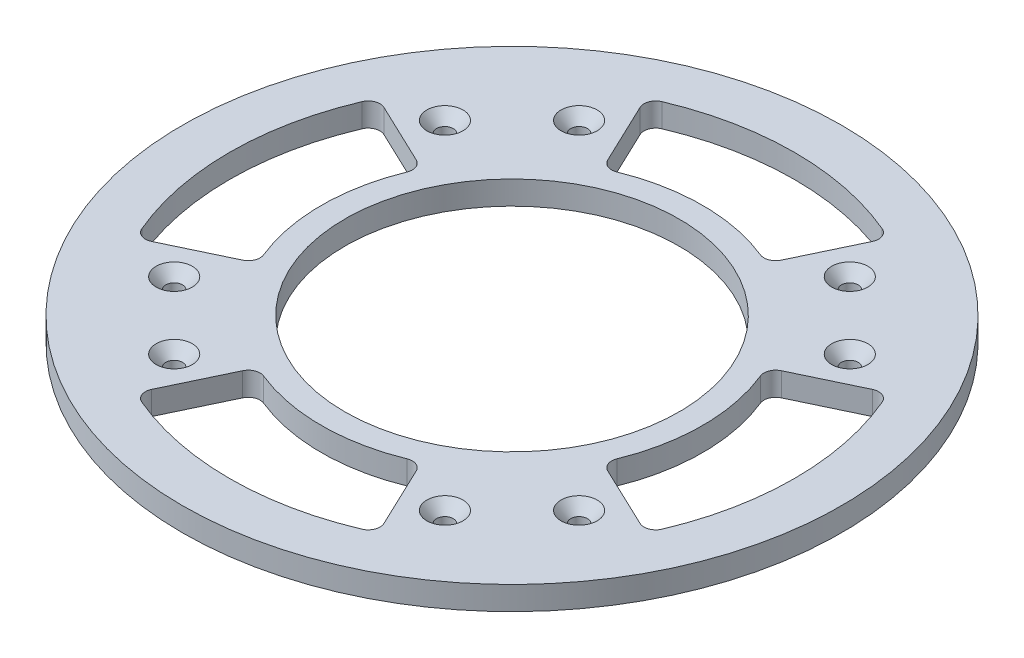
SolidWorks part; units mm, degrees
material "6061-T6 (SS)"
ref_plane "Front Plane" through (0, 0, 0) normal (0, 0, 1) x (1, 0, 0)
ref_plane "Top Plane" through (0, 0, 0) normal (0, 1, 0) x (1, 0, 0)
ref_plane "Right Plane" through (0, 0, 0) normal (1, 0, 0) x (0, 0, -1)
sketch "Sketch1" plane through (0, 0, 0) normal (0, 1, 0) x (1, 0, 0)
  line L5 (-85.725, -85.725) -> (85.725, 85.725) construction
  line L6 (-85.725, 85.725) -> (85.725, -85.725) construction
  circle A0 centre (0, 0) radius 54.61 construction
  circle A1 centre (0, 0) radius 88.9
  point P0 (0, 0)
  point P16 (-67.31, 0)
  point P18 (0, 76.2)
  dimension "D4" = 109.22
  dimension "D7" = 177.8
  dimension "D1" = 171.45
  dimension "D2" = 171.45
extrude "Boss-Extrude1" add sketch "Sketch1" along normal blind 6.35
hole_wizard "CSK for #8 Flat Head Machine Screw1" positions "Sketch3" profile "Sketch2" countersink size "#8" standard "ANSI Inch" end condition through all
sketch "Sketch3" plane through (0, 6.35, 0) normal (0, 1, 0) x (-1, 0, 0)
  line L0 (-36.5125, -54.61) -> (0, 0) construction
  line L1 (0, 0) -> (36.5125, -54.61) construction
  line L2 (36.5125, -54.61) -> (-36.5125, -54.61) construction
  line L5 (-54.61, -36.5125) -> (-54.61, 36.5125) construction
  line L8 (0, 0) -> (-54.61, -36.5125) construction
  line L11 (0, 0) -> (-54.61, 36.5125) construction
  line L14 (0, 0) -> (-36.5125, 54.61) construction
  line L15 (-36.5125, 54.61) -> (36.5125, 54.61) construction
  line L16 (36.5125, 54.61) -> (0, 0) construction
  line L17 (0, 0) -> (54.61, 36.5125) construction
  line L18 (54.61, 36.5125) -> (54.61, -36.5125) construction
  line L19 (54.61, -36.5125) -> (0, 0) construction
  point P0 (36.5125, -54.61)
  point P1 (-36.5125, -54.61)
  point P19 (36.5125, 54.61)
  point P21 (-36.5125, 54.61)
  point P23 (-54.61, -36.5125)
  point P25 (-54.61, 36.5125)
  point P27 (54.61, 36.5125)
  point P29 (54.61, -36.5125)
  dimension "D1" = 73.025
  dimension "D3" = 109.22
sketch "Sketch2" plane through (-36.5125, 6.35, -54.61) normal (1, 0, 0) x (0, 0, 1)
  line L0 (0, 0) -> (0, 6.35)
  line L1 (0, 6.35) -> (2.2479, 6.35)
  line L2 (2.2479, 6.35) -> (2.2479, 3.0265)
  line L3 (2.2479, 3.0265) -> (4.8788, 0)
  line L5 (4.8788, 0) -> (0, 0)
  line L6 (-2.2479, 3.0265) -> (-4.8788, 0) construction
  line L11 (0, -6.35) -> (0, 107.95) construction
  dimension "Thru Hole Dia." = 4.4958
  dimension "Thru Hole Depth" = 6.35
  dimension "Near C'Sink Dia." = 9.7576
  dimension "Near C'Sink Angle" = 82
ref_axis "Axis1" through (0, 0, 0) along (0, 1, 0)
pattern_circular "CirPattern1" count 2 over 360 about axis through (0, 0, 0) along (0, 1, 0) of "CSK for #8 Flat Head Machine Screw1"
sketch "Sketch4" plane through (0, 6.35, 0) normal (0, 1, 0) x (1, 0, 0)
  circle A0 centre (0, 0) radius 45.085
  dimension "D1" = 90.17
extrude "Cut-Extrude1" cut sketch "Sketch4" against normal through all
sketch "Sketch5" plane through (0, 6.35, 0) normal (0, 1, 0) x (1, 0, 0)
  line L10 (-68.8171, -32.7207) -> (-46.4515, -22.0865)
  line L11 (-68.8171, 32.7207) -> (-46.4515, 22.0865)
  arc A0 (-46.4515, 22.0865) -> (-46.4515, -22.0865) centre (0, 0) ccw
  arc A1 (-68.8171, 32.7207) -> (-68.8171, -32.7207) centre (0, 0) ccw
  circle A2 centre (0, 0) radius 88.9 construction
  circle A3 centre (0, 0) radius 45.085 construction
  circle A4 centre (-54.61, -36.5125) radius 2.2479 construction
  circle A5 centre (-54.61, 36.5125) radius 2.2479 construction
  dimension "D1" = 12.7
  dimension "D2" = 6.35
  dimension "D6" = 9.525
  dimension "D7" = 9.525
extrude "Cut-Extrude2" cut sketch "Sketch5" against normal through all
fillet "Fillet1" radius 3.175 4 edges at (-46.4515, 3.175, -22.0865) (-68.8171, 3.175, -32.7207) (-46.4515, 3.175, 22.0865) (-68.8171, 3.175, 32.7207)
pattern_circular "CirPattern2" count 4 over 360 about axis through (0, 0, 0) along (0, 1, 0) of "Cut-Extrude2", "Fillet1"
